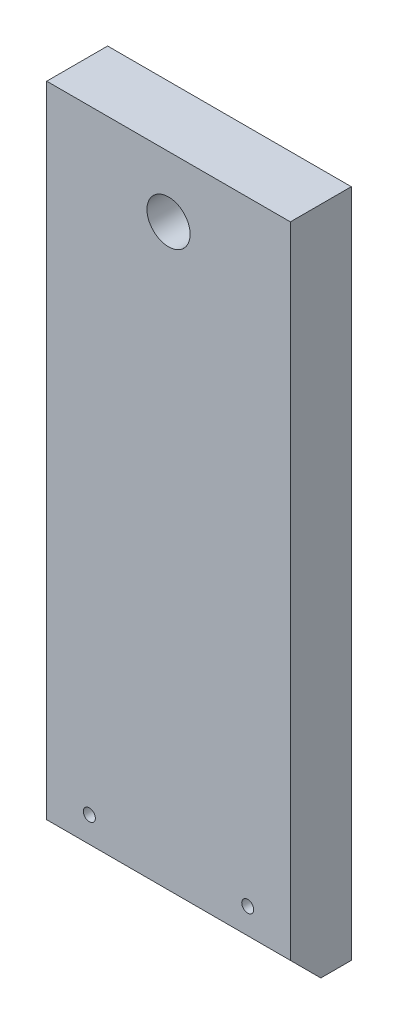
SolidWorks part; units mm, degrees
ref_plane "Front Plane" through (0, 0, 0) normal (0, 0, 1) x (1, 0, 0)
ref_plane "Top Plane" through (0, 0, 0) normal (0, 1, 0) x (1, 0, 0)
ref_plane "Right Plane" through (0, 0, 0) normal (1, 0, 0) x (0, 0, -1)
sketch "Sketch1" plane through (0, 0, 0) normal (0, 0, 1) x (1, 0, 0)
  line L1 (0, 0) -> (25.4, 0)
  line L2 (0, 0) -> (0, 69.85)
  line L3 (0, 69.85) -> (25.4, 69.85)
  line L4 (25.4, 0) -> (25.4, 69.85)
extrude "Boss-Extrude1" add sketch "Sketch1" along normal blind 6.35
sketch "Sketch2" plane through (0, 0, 6.35) normal (0, 0, 1) x (1, 0, 0)
  line L0 (25.4, 69.85) -> (0, 69.85) construction
  line L1 (0, 69.85) -> (0, 0) construction
  line L2 (0, 0) -> (25.4, 0) construction
  circle A0 centre (12.7, 63.5) radius 2.25
  circle A1 centre (4.445, 5.842) radius 0.625
  circle A2 centre (20.955, 5.842) radius 0.625
  dimension "D1" = 6.35
  dimension "D3" = 4.5
  dimension "D5" = 1.25
  dimension "D2" = 12.7
  dimension "D4" = 16.51
  dimension "D6" = 5.842
  dimension "D7" = 4.445
extrude "Cut-Extrude1" cut sketch "Sketch2" against normal blind 6.35
chamfer "Chamfer1" distance 3.175 angle 45 1 edges at (12.7, 0, 6.35)
